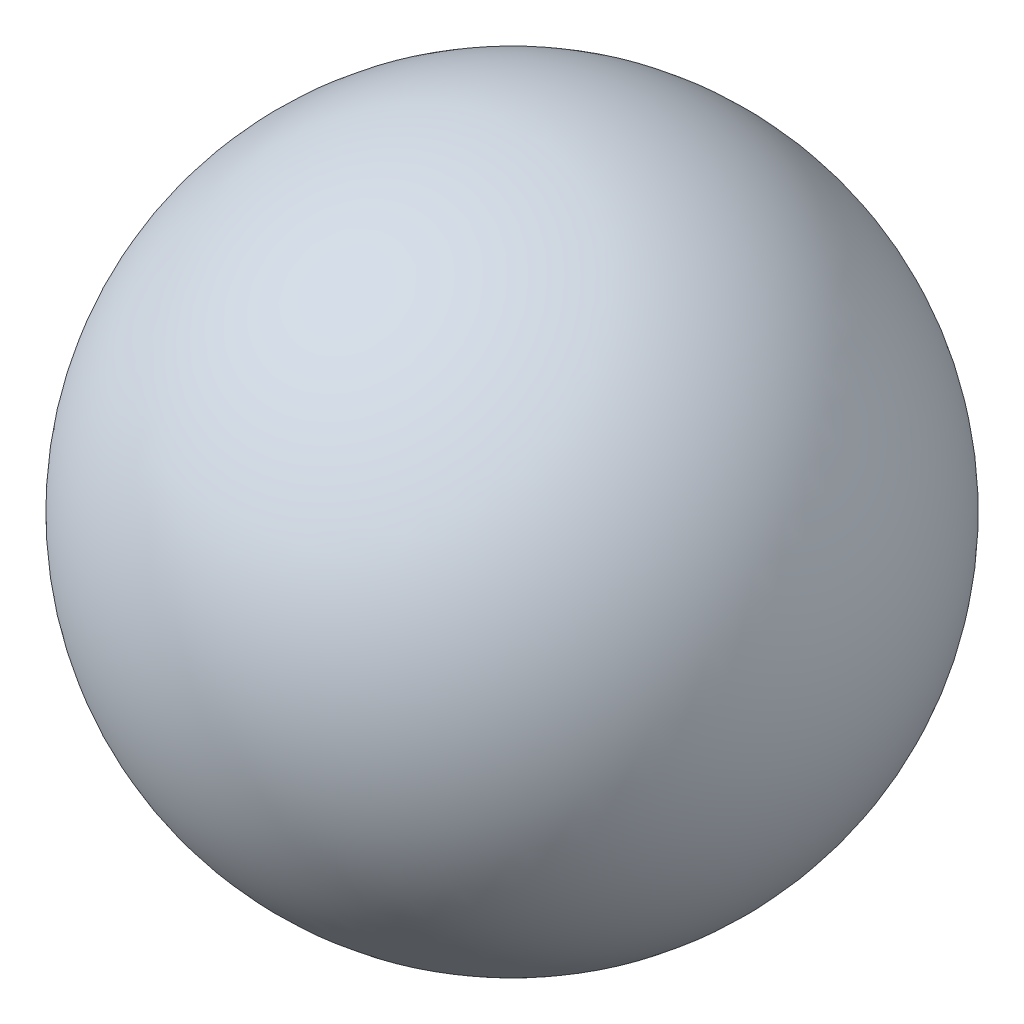
SolidWorks part; units mm, degrees
ref_plane "Front Plane" through (0, 0, 0) normal (0, 0, 1) x (1, 0, 0)
ref_plane "Top Plane" through (0, 0, 0) normal (0, 1, 0) x (1, 0, 0)
ref_plane "Right Plane" through (0, 0, 0) normal (1, 0, 0) x (0, 0, -1)
sketch "Sketch1" plane through (0, 0, 0) normal (0, 0, 1) x (1, 0, 0)
  line L0 (0, 44) -> (0, 0)
  arc A0 (0, 0) -> (0, 44) centre (0, 22) ccw
revolve "Revolve1" add sketch "Sketch1" angle 360 about L0
